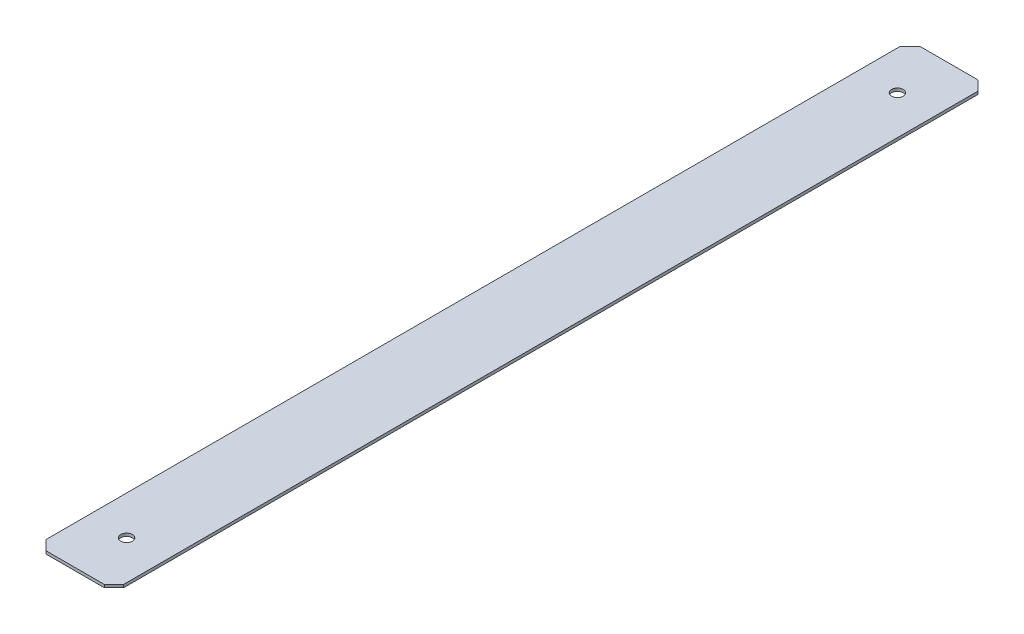
SolidWorks part; units mm, degrees
ref_plane "Front Plane" through (0, 0, 0) normal (0, 0, 1) x (1, 0, 0)
ref_plane "Top Plane" through (0, 0, 0) normal (0, 1, 0) x (1, 0, 0)
ref_plane "Right Plane" through (0, 0, 0) normal (1, 0, 0) x (0, 0, -1)
sketch "Sketch1" plane through (0, 0, 0) normal (0, 1, 0) x (1, 0, 0)
  line L1 (-20, 225) -> (20, 225)
  line L2 (-20, 225) -> (-20, -225)
  line L3 (-20, -225) -> (20, -225)
  line L4 (20, 225) -> (20, -225)
  line L5 (-20, 225) -> (20, -225) construction
  line L6 (-20, -225) -> (20, 225) construction
  point P0 (0, 0)
  dimension "D1" = 40
  dimension "D2" = 450
extrude "Boss-Extrude1" add sketch "Sketch1" along normal blind 1.5
chamfer "Chamfer1" distance 5 angle 45 4 edges at (-20, 0.75, 225) (20, 0.75, 225) (20, 0.75, -225) (-20, 0.75, -225)
sketch "Sketch2" plane through (0, 1.5, 0) normal (0, 1, 0) x (1, 0, 0)
  line L0 (-20, 198.5) -> (20, 198.5) construction
  line L1 (-20, 220) -> (-20, -220) construction
  line L2 (20, -220) -> (20, 220) construction
  line L4 (-20, 0) -> (20, 0) construction
  circle A0 centre (0, 198.5) radius 3
  circle A1 centre (0, -198.5) radius 3
  dimension "D2" = 6
  dimension "D1" = 198.5
extrude "Cut-Extrude1" cut sketch "Sketch2" against normal through all
